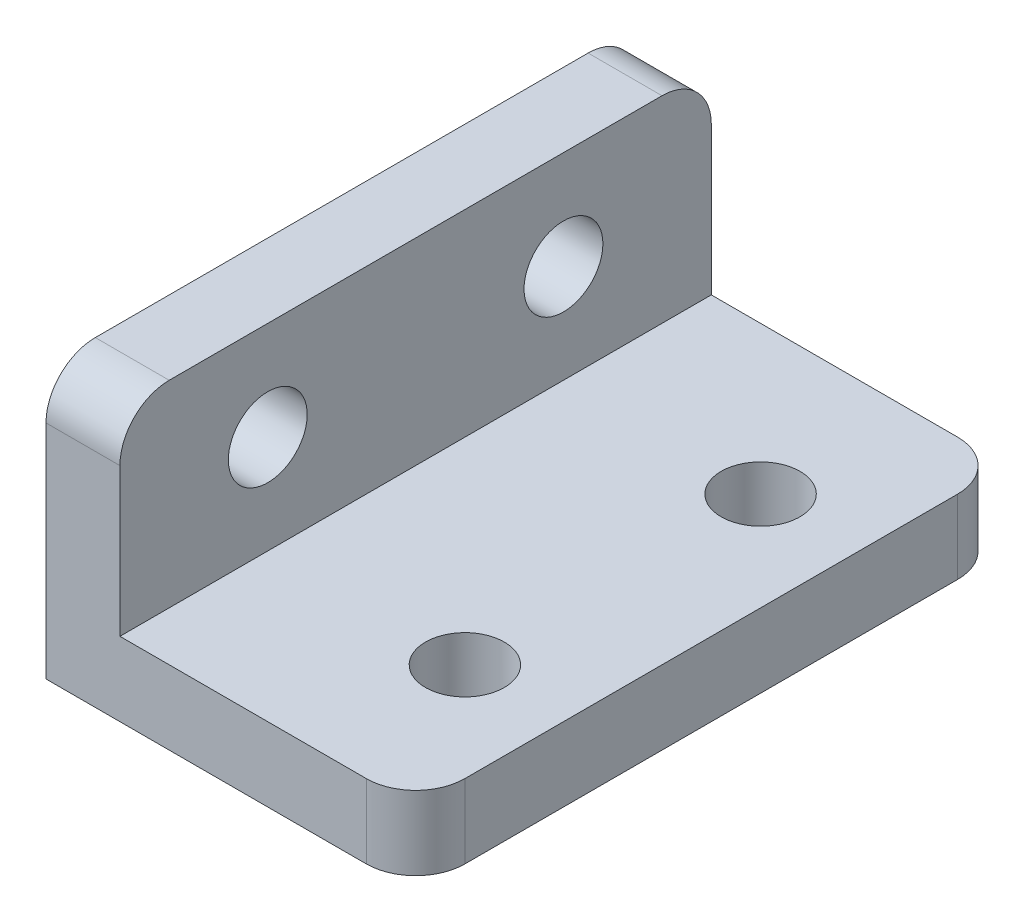
SolidWorks part; units mm, degrees
material "AISI 304"
ref_plane "前视基准面" through (0, 0, 0) normal (0, 0, 1) x (1, 0, 0)
ref_plane "上视基准面" through (0, 0, 0) normal (0, 1, 0) x (1, 0, 0)
ref_plane "右视基准面" through (0, 0, 0) normal (1, 0, 0) x (0, 0, -1)
sketch "草图1" plane through (0, 0, 0) normal (0, 0, 1) x (1, 0, 0)
  line L1 (3, 112.6916) -> (6, 112.6916)
  line L2 (3, 112.6916) -> (3, -64.3846)
  line L4 (6, 112.6916) -> (6, 104.6916)
  line L6 (3, 101.6916) -> (18, 101.6916)
  line L7 (3, 101.6916) -> (3, -61.5122)
  line L8 (6, 104.6916) -> (18, 104.6916)
  line L9 (18, 101.6916) -> (18, 104.6916)
  dimension "D1" = 3
  dimension "D2" = 3
  dimension "D3" = 8
  dimension "D4" = 12
extrude "凸台-拉伸1" add sketch "草图1" against normal blind 24 contours L6 L9 L8 L4 L1 L2 L7
sketch "草图2" plane through (6, 0, 0) normal (1, 0, 0) x (0, 0, -1)
  line L0 (24, 112.6916) -> (0, 112.6916) construction
  line L1 (0, 112.6916) -> (0, 104.6916) construction
  line L2 (24, 112.6916) -> (24, 104.6916) construction
  circle A0 centre (6, 108.6916) radius 1.6
  circle A1 centre (18, 108.6916) radius 1.6
  dimension "D1" = 3.2
  dimension "D2" = 3.2
  dimension "D3" = 4
  dimension "D4" = 6
  dimension "D5" = 6
  dimension "D6" = 4
extrude "切除-拉伸1" cut sketch "草图2" against normal blind 24
sketch "草图3" plane through (0, 104.6916, 0) normal (0, 1, 0) x (1, 0, 0)
  line L0 (18, 24) -> (18, 0) construction
  line L1 (6, 0) -> (18, 0) construction
  line L2 (6, 24) -> (18, 24) construction
  circle A0 centre (14, 6) radius 1.6
  circle A1 centre (14, 18) radius 1.6
  dimension "D1" = 3.2
  dimension "D2" = 3.2
  dimension "D3" = 4
  dimension "D4" = 4
  dimension "D5" = 6
  dimension "D6" = 6
extrude "切除-拉伸2" cut sketch "草图3" against normal blind 24
fillet "圆角1" radius 2 4 edges at (18, 103.1916, -24) (18, 103.1916, 0) (4.5, 112.6916, -24) (4.5, 112.6916, 0)
